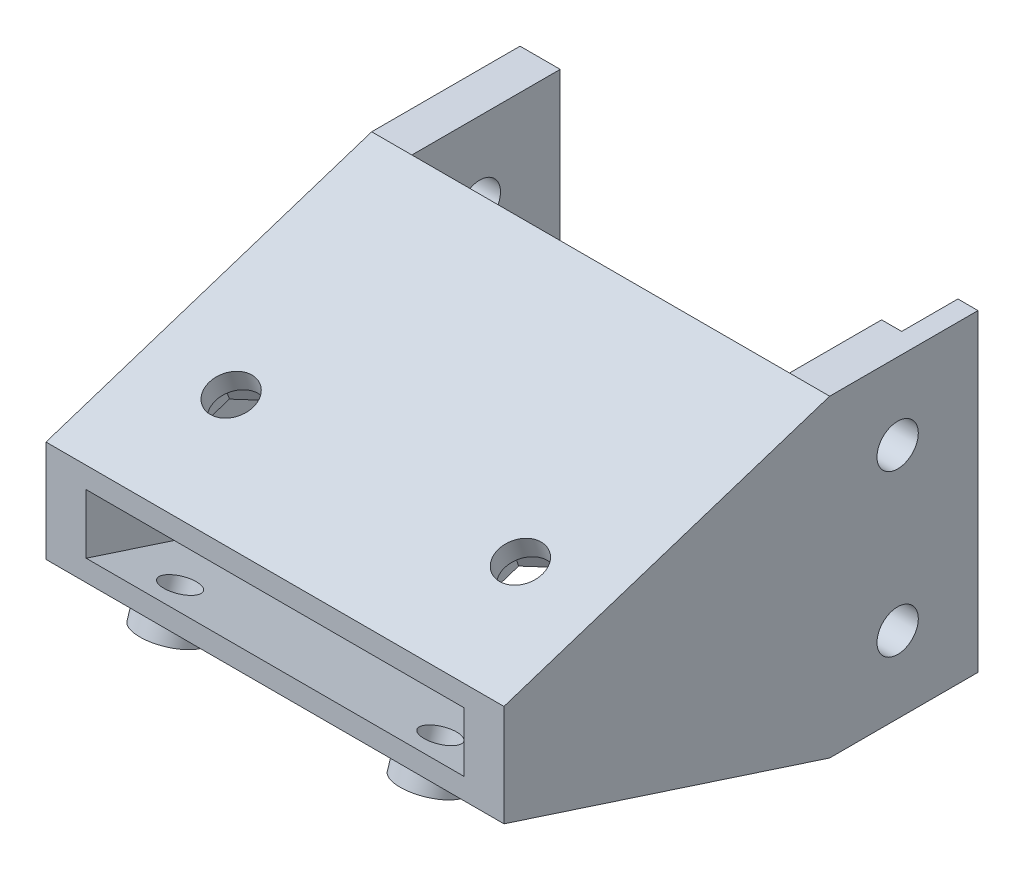
SolidWorks part; units mm, degrees
ref_plane "Front Plane" through (0, 0, 0) normal (0, 0, 1) x (1, 0, 0)
ref_plane "Top Plane" through (0, 0, 0) normal (0, 1, 0) x (1, 0, 0)
ref_plane "Right Plane" through (0, 0, 0) normal (1, 0, 0) x (0, 0, -1)
sketch "Sketch1" plane through (0, 0, 0) normal (0, 0, 1) x (1, 0, 0)
  line L1 (18.0975, 12.3825) -> (-18.0975, 12.3825)
  line L2 (18.0975, 12.3825) -> (18.0975, -12.3825)
  line L3 (18.0975, -12.3825) -> (-18.0975, -12.3825)
  line L4 (-18.0975, 12.3825) -> (-18.0975, -12.3825)
  line L5 (18.0975, 12.3825) -> (-18.0975, -12.3825) construction
  line L6 (18.0975, -12.3825) -> (-18.0975, 12.3825) construction
  point P0 (0, 0)
  dimension "D1" = 36.195
  dimension "D2" = 24.765
extrude "Boss-Extrude1" add sketch "Sketch1" along normal blind 43.815
sketch "Sketch2" plane through (0, 0, 0) normal (0, 0, -1) x (-1, 0, 0)
  line L0 (-18.0975, 12.3825) -> (18.0975, 12.3825) construction
  line L1 (-14.9225, 12.3825) -> (14.9225, 12.3825)
  line L2 (-14.9225, 12.3825) -> (-14.9225, -12.3825)
  line L3 (-14.9225, -12.3825) -> (14.9225, -12.3825)
  line L4 (14.9225, 12.3825) -> (14.9225, -12.3825)
  line L5 (18.0975, -12.3825) -> (-18.0975, -12.3825) construction
  line L6 (-18.0975, -12.3825) -> (-18.0975, 12.3825) construction
  line L7 (18.0975, 12.3825) -> (18.0975, -12.3825) construction
  dimension "D1" = 3.175
  dimension "D2" = 3.175
extrude "Cut-Extrude2" cut sketch "Sketch2" against normal through all
sketch "Sketch3" plane through (-14.9225, 0, 0) normal (1, 0, 0) x (0, 0, -1)
  line L0 (-3.0148, 0) -> (-55.7953, 0) construction
  line L1 (-43.815, -2.3495) -> (-43.815, -4.0187)
  line L2 (-43.815, -4.0187) -> (-18.0739, -12.3825)
  line L3 (-18.0739, -12.3825) -> (-18.0739, -10.7133)
  line L4 (-43.815, -2.3495) -> (-18.0739, -10.7133)
  line L5 (-43.815, -12.3825) -> (-43.815, 12.3825) construction
  line L6 (-18.0739, 12.3825) -> (-18.0739, 10.7133)
  line L7 (-43.815, 4.0187) -> (-18.0739, 12.3825)
  line L8 (-43.815, 2.3495) -> (-18.0739, 10.7133)
  line L9 (-43.815, 2.3495) -> (-43.815, 4.0187)
  line L10 (-43.815, -12.3825) -> (0, -12.3825) construction
  dimension "D1" = 1.5875
  dimension "D3" = 18
  dimension "D4" = 2.3495
extrude "Boss-Extrude2" add sketch "Sketch3" along normal up to next
sketch "Sketch4" plane through (-14.9225, 0, 0) normal (1, 0, 0) x (0, 0, -1)
  line L0 (-46.355, -3.1934) -> (-10.1197, -14.9669)
  line L1 (-10.1197, -14.9669) -> (-46.355, -14.9669)
  line L2 (-46.355, -14.9669) -> (-46.355, -3.1934)
  line L3 (-43.815, -4.0187) -> (-18.0739, -12.3825) construction
  line L4 (-43.815, -12.3825) -> (-43.815, -4.0187) construction
  line L5 (-1.4091, 0) -> (-49.2065, 0) construction
  line L6 (-46.355, 14.9669) -> (-46.355, 3.1934)
  line L7 (-10.1197, 14.9669) -> (-46.355, 14.9669)
  line L8 (-46.355, 3.1934) -> (-10.1197, 14.9669)
  dimension "D1" = 38.1
  dimension "D2" = 2.54
extrude "Cut-Extrude3" cut sketch "Sketch4" against normal through all and the other way through all
sketch "Sketch15" plane through (0, -16.5119, 5.365) normal (0, -0.9511, 0.309) x (1, 0, 0)
  line L0 (18.0975, 40.4287) -> (-18.0975, 40.4287) construction
  line L1 (-18.0975, 13.3629) -> (-18.0975, 40.4287) construction
  circle A0 centre (-10.287, 38.0157) radius 2.413
  circle A1 centre (10.287, 38.0157) radius 2.413
  circle A2 centre (10.287, 25.5697) radius 2.413
  circle A3 centre (-10.287, 25.5697) radius 2.413
  dimension "D2" = 4.826
  dimension "D5" = 2.413
  dimension "D6" = 12.446
  dimension "D7" = 20.574
  dimension "D8" = 7.8105
extrude "Boss-Extrude4" add sketch "Sketch15" along normal blind 1.27
hole_wizard "#2 Clearance Hole1" positions "Sketch17" profile "Sketch16" hole size "#2" standard "ANSI Inch"
sketch "Sketch17" plane through (0, -17.7197, 5.7575) normal (0, -0.9511, 0.309) x (-1, 0, 0)
  point P0 (10.287, -25.5697)
  point P3 (10.287, -38.0157)
  point P6 (-10.287, -38.0157)
  point P9 (-10.287, -25.5697)
sketch "Sketch16" plane through (-10.287, -9.8182, 30.0757) normal (1, 0, 0) x (0, -0.309, -0.9511)
  line L0 (0, 0) -> (0, 6.1467)
  line L1 (0, 6.1467) -> (1.3525, 5.334)
  line L2 (1.3525, 5.334) -> (1.3525, 0)
  line L5 (1.3525, 0) -> (0, 0)
  line L10 (0, 6.1467) -> (-1.3525, 5.334) construction
  line L11 (0, -6.35) -> (0, 107.95) construction
  dimension "Hole Dia." = 2.7051
  dimension "Hole Depth" = 5.334
  dimension "Drill Angle" = 118
sketch "Sketch5" plane through (0, -16.5119, 5.365) normal (0, -0.9511, 0.309) x (1, 0, 0)
  line L0 (0, 37.7905) -> (0, 9.8805) construction
  line L1 (18.0975, 40.4287) -> (10.287, 40.4287) construction
  line L2 (14.9225, 13.3629) -> (-14.9225, 13.3629) construction
  line L3 (-10.16, 13.3629) -> (10.16, 13.3629)
  line L4 (-10.16, 13.3629) -> (-10.16, 21.7597)
  line L5 (-10.16, 21.7597) -> (10.16, 21.7597)
  line L6 (10.16, 13.3629) -> (10.16, 21.7597)
  circle A0 centre (-10.287, 38.0157) radius 0.5715
  circle A1 centre (10.287, 38.0157) radius 0.5715
  circle A2 centre (10.287, 25.5697) radius 0.5715
  circle A3 centre (-10.287, 25.5697) radius 0.5715
  dimension "D1" = 1.143
  dimension "D2" = 10.287
  dimension "D3" = 2.413
  dimension "D6" = 20.32
  dimension "D7" = 3.81
  dimension "D4" = 2
  dimension "D5" = 2
extrude "Cut-Extrude4" cut sketch "Sketch5" against normal up to surface (1.5875 mm away) up to face at (-10.287, -7.5185, 27.9063)
hole_wizard "#4 Clearance Hole1" positions "Sketch7" profile "Sketch6" hole size "#4" standard "ANSI Inch"
sketch "Sketch7" plane through (14.9225, 0, 0) normal (-1, 0, 0) x (0, 0, 1)
  line L0 (0, 12.3825) -> (0, -12.3825) construction
  line L3 (-1.8736, 0) -> (6.9872, 0) construction
  point P0 (12.7, 6.35)
  point P2 (12.7, -6.35)
  dimension "D1" = 12.7
  dimension "D2" = 12.7
sketch "Sketch6" plane through (14.9225, 6.35, 12.7) normal (0, 1, 0) x (0, 0, 1)
  line L0 (0, 0) -> (0, 10.8866)
  line L1 (0, 10.8866) -> (1.6319, 9.906)
  line L2 (1.6319, 9.906) -> (1.6319, 0)
  line L5 (1.6319, 0) -> (0, 0)
  line L10 (0, 10.8866) -> (-1.632, 9.906) construction
  line L11 (0, -6.35) -> (0, 107.95) construction
  dimension "Hole Dia." = 3.2639
  dimension "Hole Depth" = 9.906
  dimension "Drill Angle" = 118
mirror "Mirror2" about plane through (0, 0, 0) normal (1, 0, 0) of "#4 Clearance Hole1"
sketch "Sketch8" plane through (-18.0975, 0, 0) normal (-1, 0, 0) x (0, 0, 1)
  line L0 (18.0739, -12.3825) -> (0, -12.3825) construction
  line L1 (0, 12.3825) -> (6.35, 12.3825)
  line L2 (0, 12.3825) -> (0, -12.3825)
  line L3 (0, -12.3825) -> (6.35, -12.3825)
  line L4 (6.35, 12.3825) -> (6.35, -12.3825)
  dimension "D1" = 6.35
extrude "Cut-Extrude5" cut sketch "Sketch8" against normal through all
sketch "Sketch12" plane through (0, 15.002, 4.8745) normal (0, -0.9511, -0.309) x (-1, 0, 0)
  line L0 (-14.9225, -40.9445) -> (-14.9225, -13.8787) construction
  line L1 (-14.9225, -36.4995) -> (-6.0325, -36.4995)
  line L2 (-14.9225, -36.4995) -> (-14.9225, -27.6095)
  line L3 (-14.9225, -27.6095) -> (-6.0325, -27.6095)
  line L4 (-6.0325, -36.4995) -> (-6.0325, -27.6095)
  line L5 (-14.9225, -36.4995) -> (-6.0325, -27.6095) construction
  line L6 (-14.9225, -27.6095) -> (-6.0325, -36.4995) construction
  line L7 (14.9225, -27.6095) -> (6.0325, -27.6095)
  line L8 (14.9225, -27.6095) -> (14.9225, -36.4995)
  line L9 (14.9225, -36.4995) -> (6.0325, -36.4995)
  line L10 (6.0325, -27.6095) -> (6.0325, -36.4995)
  line L11 (14.9225, -27.6095) -> (6.0325, -36.4995) construction
  line L12 (14.9225, -36.4995) -> (6.0325, -27.6095) construction
  line L13 (14.9225, -40.9445) -> (14.9225, -13.8787) construction
  line L14 (-14.9225, -40.9445) -> (14.9225, -40.9445) construction
  point P0 (-10.4775, -32.0545)
  point P6 (10.4775, -32.0545)
  dimension "D1" = 8.89
  dimension "D2" = 8.89
  dimension "D3" = 8.89
  dimension "D4" = 8.89
  dimension "D5" = 0
  dimension "D6" = 0
  dimension "D7" = 4.445
  dimension "D8" = 4.445
extrude "Boss-Extrude3" add sketch "Sketch12" along normal blind 2.54
hole_wizard "#4 Clearance Hole2" positions "Sketch11" profile "Sketch10" hole size "#4" standard "ANSI Inch"
sketch "Sketch11" plane through (0, 16.5119, 5.365) normal (0, 0.9511, 0.309) x (1, 0, 0)
  line L0 (0, 0) -> (0, -51.1785) construction
  line L3 (14.9225, -40.9445) -> (-14.9225, -40.9445) construction
  point P0 (-11.43, -32.0545)
  point P2 (11.43, -32.0545)
  dimension "D1" = 22.86
  dimension "D2" = 8.89
sketch "Sketch10" plane through (-11.43, 6.6065, 35.8507) normal (1, 0, 0) x (0, -0.309, 0.9511)
  line L0 (0, 0) -> (0, 4.1275)
  line L1 (0, 4.1275) -> (1.7272, 4.1275)
  line L2 (1.7272, 4.1275) -> (1.7272, 0)
  line L5 (1.7272, 0) -> (0, 0)
  line L11 (0, -6.35) -> (0, 107.95) construction
  dimension "Thru Hole Dia." = 3.4544
  dimension "Thru Hole Depth" = 4.1275
sketch "Sketch13" plane through (0, 12.5864, 4.0896) normal (0, -0.9511, -0.309) x (-1, 0, 0)
  line L1 (-8.2931, -33.8656) -> (-8.2931, -30.2434)
  line L2 (-8.2931, -30.2434) -> (-11.43, -28.4323)
  line L3 (-11.43, -28.4323) -> (-14.5669, -30.2434)
  line L4 (-14.5669, -30.2434) -> (-14.5669, -33.8656)
  line L5 (-14.5669, -33.8656) -> (-11.43, -35.6767)
  line L6 (-11.43, -35.6767) -> (-8.2931, -33.8656)
  line L7 (8.2931, -33.8656) -> (11.43, -35.6767)
  line L8 (11.43, -35.6767) -> (14.5669, -33.8656)
  line L9 (14.5669, -33.8656) -> (14.5669, -30.2434)
  line L10 (14.5669, -30.2434) -> (11.43, -28.4323)
  line L11 (11.43, -28.4323) -> (8.2931, -30.2434)
  line L12 (8.2931, -30.2434) -> (8.2931, -33.8656)
  circle A0 centre (-11.43, -32.0545) radius 3.1369 construction
  circle A1 centre (11.43, -32.0545) radius 3.1369 construction
  dimension "D1" = 6.2738
  dimension "D2" = 6.2738
extrude "Cut-Extrude7" cut sketch "Sketch13" against normal blind 2.54
sketch "Sketch18" plane through (0, 0, 6.35) normal (0, 0, -1) x (-1, 0, 0)
  line L1 (-14.9225, 12.3825) -> (-16.51, 12.3825)
  line L2 (-14.9225, 12.3825) -> (-14.9225, 6.0325)
  line L3 (-14.9225, 6.0325) -> (-16.51, 6.0325)
  line L4 (-16.51, 12.3825) -> (-16.51, 6.0325)
  line L5 (14.9225, -12.3825) -> (16.51, -12.3825)
  line L6 (14.9225, -12.3825) -> (14.9225, -6.0325)
  line L7 (14.9225, -6.0325) -> (16.51, -6.0325)
  line L8 (16.51, -12.3825) -> (16.51, -6.0325)
  dimension "D1" = 1.5875
  dimension "D2" = 6.35
extrude "Cut-Extrude8" cut sketch "Sketch18" against normal blind 4.445
